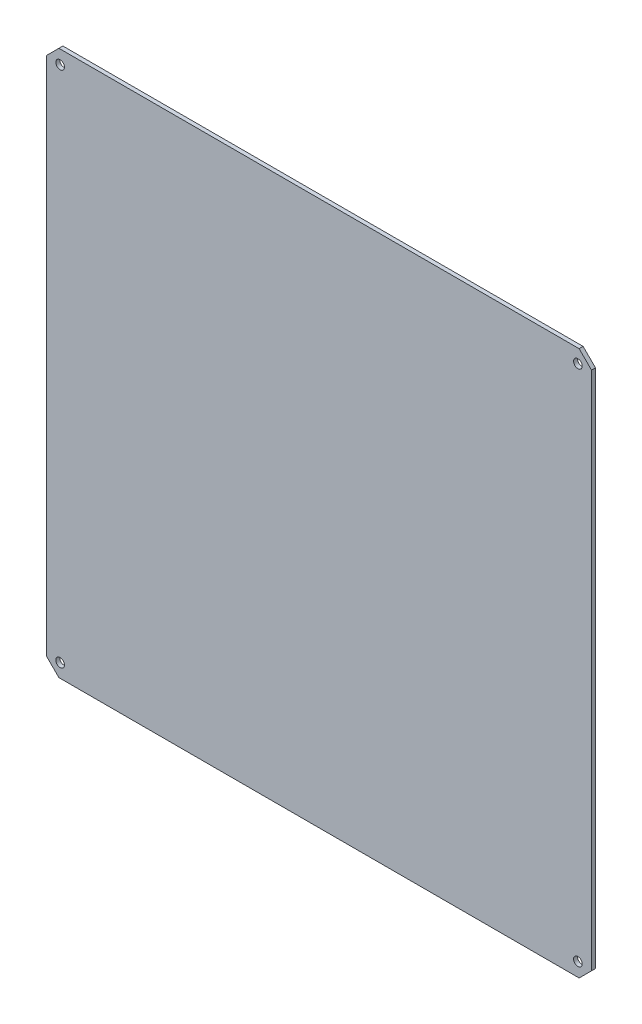
SolidWorks part; units mm, degrees
material "Żywica poliestrowa"
ref_plane "Płaszczyzna przednia" through (0, 0, 0) normal (0, 0, 1) x (1, 0, 0)
ref_plane "Płaszczyzna górna" through (0, 0, 0) normal (0, 1, 0) x (1, 0, 0)
ref_plane "Płaszczyzna prawa" through (0, 0, 0) normal (1, 0, 0) x (0, 0, -1)
sketch "Szkic1" plane through (0, 0, 0) normal (0, 0, 1) x (1, 0, 0)
  line L1 (-110, -110) -> (110, -110)
  line L2 (-110, -110) -> (-110, 110)
  line L3 (-110, 110) -> (110, 110)
  line L4 (110, -110) -> (110, 110)
  line L5 (0, 110) -> (0, -110) construction
  line L6 (-110, 0) -> (110, 0) construction
  line L7 (-104.5, -104.5) -> (104.5, -104.5) construction
  line L8 (-104.5, -104.5) -> (-104.5, 104.5) construction
  line L9 (-104.5, 104.5) -> (104.5, 104.5) construction
  line L10 (104.5, -104.5) -> (104.5, 104.5) construction
  line L11 (0, 104.5) -> (0, -104.5) construction
  line L12 (-104.5, 0) -> (104.5, 0) construction
  circle A0 centre (104.5, 104.5) radius 1.75
  circle A1 centre (-104.5, 104.5) radius 1.75
  circle A2 centre (-104.5, -104.5) radius 1.75
  circle A3 centre (104.5, -104.5) radius 1.75
  point P0 (0, 0)
  point P4 (0, 0)
  dimension "D3" = 3.5
  dimension "D1" = 220
  dimension "D2" = 209
extrude "Dodanie-wyciągnięcie1" add sketch "Szkic1" along normal blind 1.6
chamfer "Sfazowanie1" distance 5 angle 45 4 edges at (-110, -110, 0.8) (110, -110, 0.8) (-110, 110, 0.8) (110, 110, 0.8)
